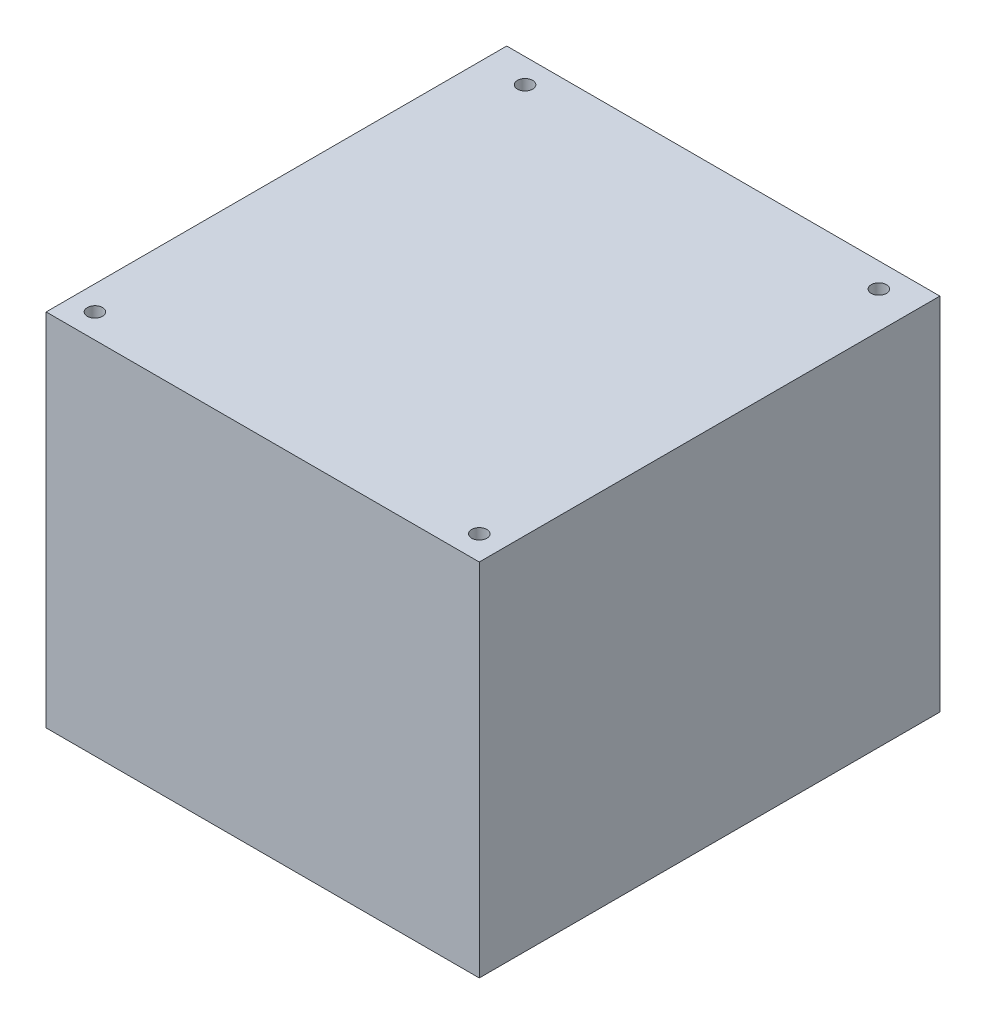
SolidWorks part; units mm, degrees
ref_plane "Front" through (0, 0, 0) normal (0, 0, 1) x (1, 0, 0)
ref_plane "Top" through (0, 0, 0) normal (0, 1, 0) x (1, 0, 0)
ref_plane "Right" through (0, 0, 0) normal (1, 0, 0) x (0, 0, -1)
sketch "Sketch1" plane through (0, 0, 0) normal (0, 1, 0) x (1, 0, 0)
  line L1 (-45.085, -47.9425) -> (45.085, -47.9425)
  line L2 (-45.085, -47.9425) -> (-45.085, 47.9425)
  line L3 (-45.085, 47.9425) -> (45.085, 47.9425)
  line L4 (45.085, -47.9425) -> (45.085, 47.9425)
  line L5 (-45.085, -47.9425) -> (45.085, 47.9425) construction
  line L6 (-45.085, 47.9425) -> (45.085, -47.9425) construction
  point P0 (0, 0)
  dimension "D1" = 90.17
  dimension "D2" = 95.885
extrude "Boss-Extrude1" add sketch "Sketch1" along normal blind 75
sketch "Sketch2" plane through (0, 75, 0) normal (0, 1, 0) x (1, 0, 0)
  line L0 (-45.085, 47.9425) -> (-45.085, -47.9425) construction
  line L1 (-45.085, -47.9425) -> (45.085, -47.9425) construction
  circle A0 centre (-40.005, -42.8625) radius 1.5875
  circle A1 centre (40.005, -42.8625) radius 1.5875
  circle A2 centre (-36.195, 42.8625) radius 1.5875
  circle A3 centre (37.465, 42.8625) radius 1.5875
  dimension "D1" = 3.175
  dimension "D2" = 5.08
  dimension "D3" = 5.08
  dimension "D4" = 80.01
  dimension "D5" = 85.725
  dimension "D6" = 3.81
  dimension "D7" = 73.66
extrude "Cut-Extrude1" cut sketch "Sketch2" against normal through all
